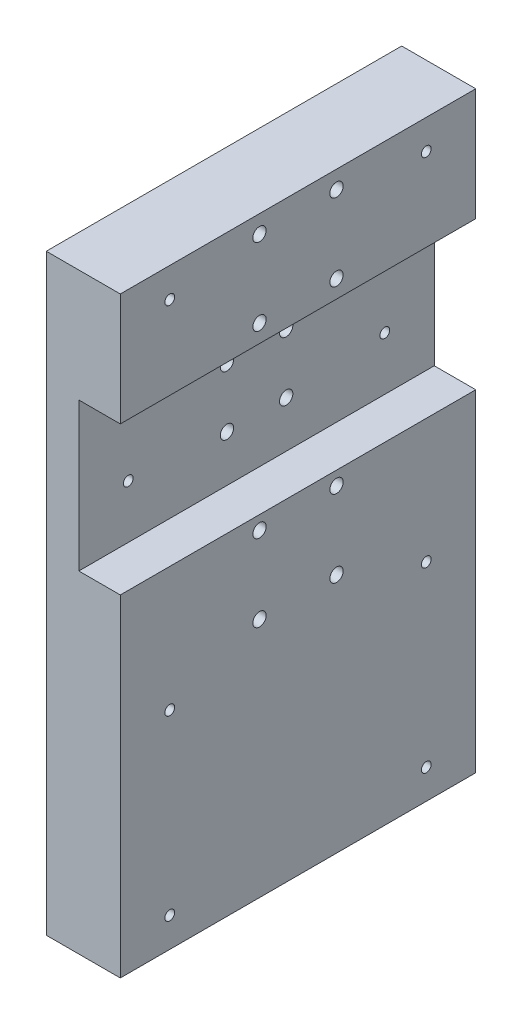
SolidWorks part; units mm, degrees
ref_plane "Front Plane" through (0, 0, 0) normal (0, 0, 1) x (1, 0, 0)
ref_plane "Top Plane" through (0, 0, 0) normal (0, 1, 0) x (1, 0, 0)
ref_plane "Right Plane" through (0, 0, 0) normal (1, 0, 0) x (0, 0, -1)
sketch "Sketch1" plane through (0, 0, 0) normal (0, 0, 1) x (1, 0, 0)
  line L0 (0, 0) -> (0, 200)
  line L1 (0, 200) -> (25, 200)
  line L2 (25, 200) -> (25, 162)
  line L3 (25, 162) -> (11, 162)
  line L4 (11, 162) -> (11, 112)
  line L5 (11, 112) -> (25, 112)
  line L6 (25, 112) -> (25, 0)
  line L7 (25, 0) -> (0, 0)
  dimension "D1" = 200
  dimension "D2" = 11
  dimension "D3" = 38
  dimension "D4" = 25
  dimension "D5" = 50
extrude "Boss-Extrude1" add sketch "Sketch1" along normal blind 120 contours L0 L1 L2 L3 L4 L5 L6 L7
sketch "Sketch2" plane through (0, 0, 0) normal (-1, 0, 0) x (0, 0, 1)
  line L0 (60, 200) -> (60, 0) construction
  line L1 (120, 200) -> (0, 200) construction
  line L2 (120, 0) -> (0, 0) construction
  point P6 (73, 194)
  point P7 (73, 168)
  point P8 (70, 147.7)
  point P9 (70, 127.7)
  point P10 (73, 107.4)
  point P11 (73, 81.4)
  point P12 (47, 81.4)
  point P13 (47, 107.4)
  point P14 (50, 127.7)
  point P15 (50, 147.7)
  point P16 (47, 168)
  point P17 (47, 194)
  dimension "D1" = 6
  dimension "D2" = 26
  dimension "D3" = 46.3
  dimension "D4" = 20
  dimension "D5" = 20.3
  dimension "D6" = 26
  dimension "D7" = 13
  dimension "D8" = 10
hole_wizard "CBORE for M4 SHCS4" positions "3DSketch2" profile "Sketch4" counterbore size "M4" standard "ANSI Metric" end condition through all
sketch3d "3DSketch2"
  point P0 (0, 194, 73)
  point P3 (0, 168, 73)
  point P6 (0, 147.7, 70)
  point P9 (0, 127.7, 70)
  point P12 (0, 107.4, 73)
  point P15 (0, 81.4, 73)
  point P18 (0, 81.4, 47)
  point P21 (0, 107.4, 47)
  point P24 (0, 127.7, 50)
  point P27 (0, 147.7, 50)
  point P30 (0, 168, 47)
  point P33 (0, 194, 47)
sketch "Sketch4" plane through (0, 194, 73) normal (0, 1, 0) x (0, 0, 1)
  line L0 (0, 0) -> (0, 25)
  line L1 (0, 25) -> (2.25, 25)
  line L3 (2.25, 25) -> (2.25, 4)
  line L4 (2.25, 4) -> (4, 4)
  line L5 (4, 4) -> (4, 0)
  line L7 (4, 0) -> (0, 0)
  line L11 (0, -6.35) -> (0, 107.95) construction
  dimension "Thru Hole Dia." = 4.5
  dimension "Thru Hole Depth" = 25
  dimension "C'Bore Dia." = 8
  dimension "C'Bore Depth" = 4
sketch "Sketch5" plane through (0, 0, 0) normal (-1, 0, 0) x (0, 0, 1)
  line L0 (16.7, 200) -> (16.7, 0) construction
  line L1 (120, 200) -> (0, 200) construction
  line L2 (120, 0) -> (0, 0) construction
  line L3 (60, 200) -> (60, 0) construction
  line L4 (60, 200) -> (60, 0) construction
  line L5 (103.3, 200) -> (103.3, 0) construction
  point P12 (16.7, 190)
  point P13 (103.3, 10)
  point P14 (16.7, 130)
  point P15 (16.7, 70)
  point P16 (16.7, 10)
  point P17 (103.3, 70)
  point P18 (103.3, 130)
  point P19 (103.3, 190)
  dimension "D1" = 43.3
  dimension "D2" = 10
  dimension "D3" = 4
hole_wizard "M4 Tapped Hole1" positions "3DSketch3" profile "Sketch6" tap size "M4" standard "ISO" end condition through all
sketch3d "3DSketch3"
  point P0 (0, 190, 16.7)
  point P3 (0, 130, 16.7)
  point P6 (0, 70, 16.7)
  point P9 (0, 10, 16.7)
  point P12 (0, 10, 103.3)
  point P15 (0, 70, 103.3)
  point P18 (0, 130, 103.3)
  point P21 (0, 190, 103.3)
sketch "Sketch6" plane through (0, 190, 16.7) normal (0, 1, 0) x (0, 0, 1)
  line L0 (0, 0) -> (0, 25)
  line L1 (0, 25) -> (1.65, 25)
  line L2 (1.65, 25) -> (1.65, 0)
  line L5 (1.65, 0) -> (0, 0)
  line L11 (0, -6.35) -> (0, 107.95) construction
  dimension "Thread Major Dia." = 3.3
  dimension "Thru Tap Drill Depth" = 25
ref_plane "Plane1" through (0, 0, 60) normal (0, 0, -1) x (-1, 0, 0)
sketch "Sketch7" plane through (0, 0, 0) normal (0, -1, 0) x (1, 0, 0)
  line L0 (12.5, 120) -> (12.5, 0) construction
  line L1 (25, 120) -> (0, 120) construction
  line L2 (25, 0) -> (0, 0) construction
  line L3 (25, 60) -> (0, 60) construction
  line L4 (25, 120) -> (25, 0) construction
  line L5 (0, 120) -> (0, 0) construction
  point P12 (12.5, 60)
  point P13 (12.5, 90)
  point P14 (12.5, 30)
  dimension "D1" = 30
hole_wizard "M5 Tapped Hole1" positions "3DSketch4" profile "Sketch8" tap size "M5" standard "ISO"
sketch3d "3DSketch4"
  point P0 (12.5, 0, 90)
  point P3 (12.5, 0, 60)
  point P6 (12.5, 0, 30)
sketch "Sketch8" plane through (12.5, 0, 90) normal (1, 0, 0) x (0, 0, -1)
  line L0 (0, 0) -> (0, 18.6618)
  line L1 (0, 18.6618) -> (2.1, 17.4)
  line L2 (2.1, 17.4) -> (2.1, 0)
  line L5 (2.1, 0) -> (0, 0)
  line L10 (0, 18.6618) -> (-2.1, 17.4) construction
  line L11 (0, -6.35) -> (0, 107.95) construction
  dimension "Tap Drill Dia." = 4.2
  dimension "Tap Drill Depth" = 17.4
  dimension "Drill Angle" = 118
